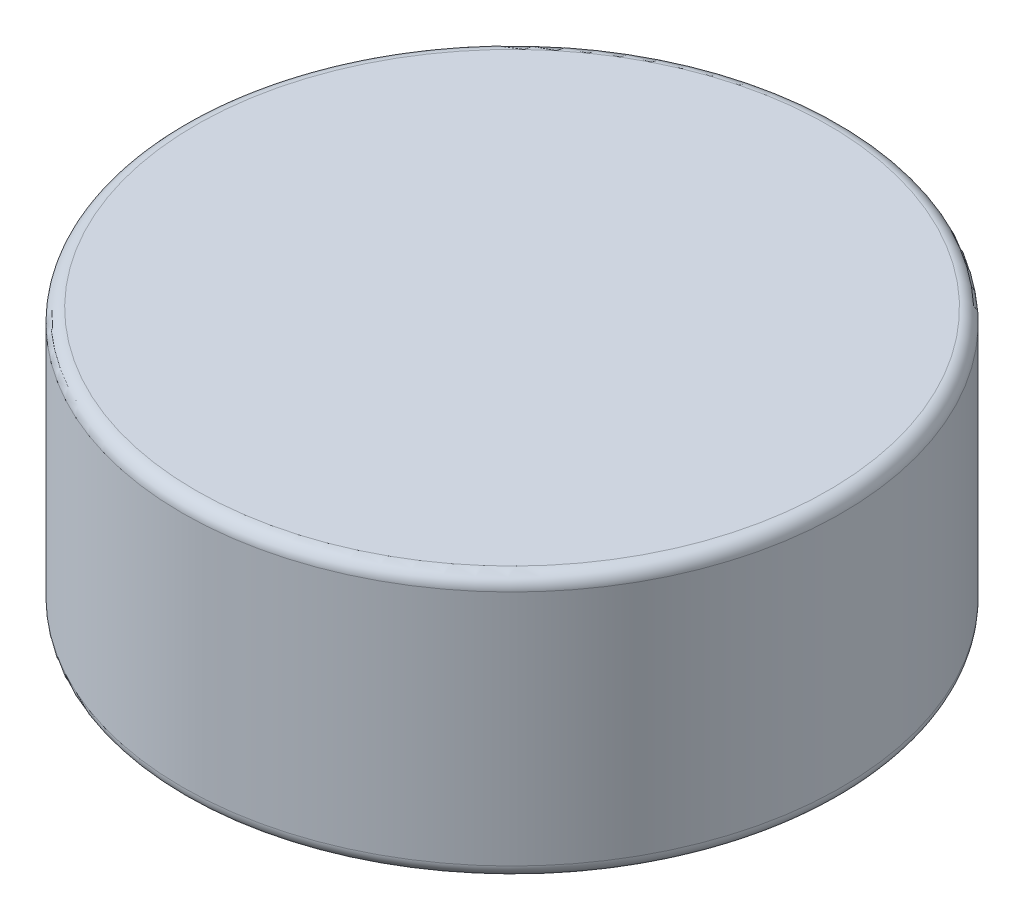
SolidWorks part; units mm, degrees
ref_plane "Front Plane" through (0, 0, 0) normal (0, 0, 1) x (1, 0, 0)
ref_plane "Top Plane" through (0, 0, 0) normal (0, 1, 0) x (1, 0, 0)
ref_plane "Right Plane" through (0, 0, 0) normal (1, 0, 0) x (0, 0, -1)
sketch "Sketch1" plane through (0, 0, 0) normal (0, 1, 0) x (1, 0, 0)
  circle A0 centre (0, 0) radius 25
extrude "Boss-Extrude1" add sketch "Sketch1" against normal blind 20
fillet "Fillet3" radius 1 2 edges at (0, -20, 25) (0, 0, 25)
sketch "Sketch2" plane through (0, -20, 0) normal (0, -1, 0) x (1, 0, 0)
  circle A0 centre (0, 0) radius 3
extrude "Cut-Extrude1" cut sketch "Sketch2" against normal blind 12.5
